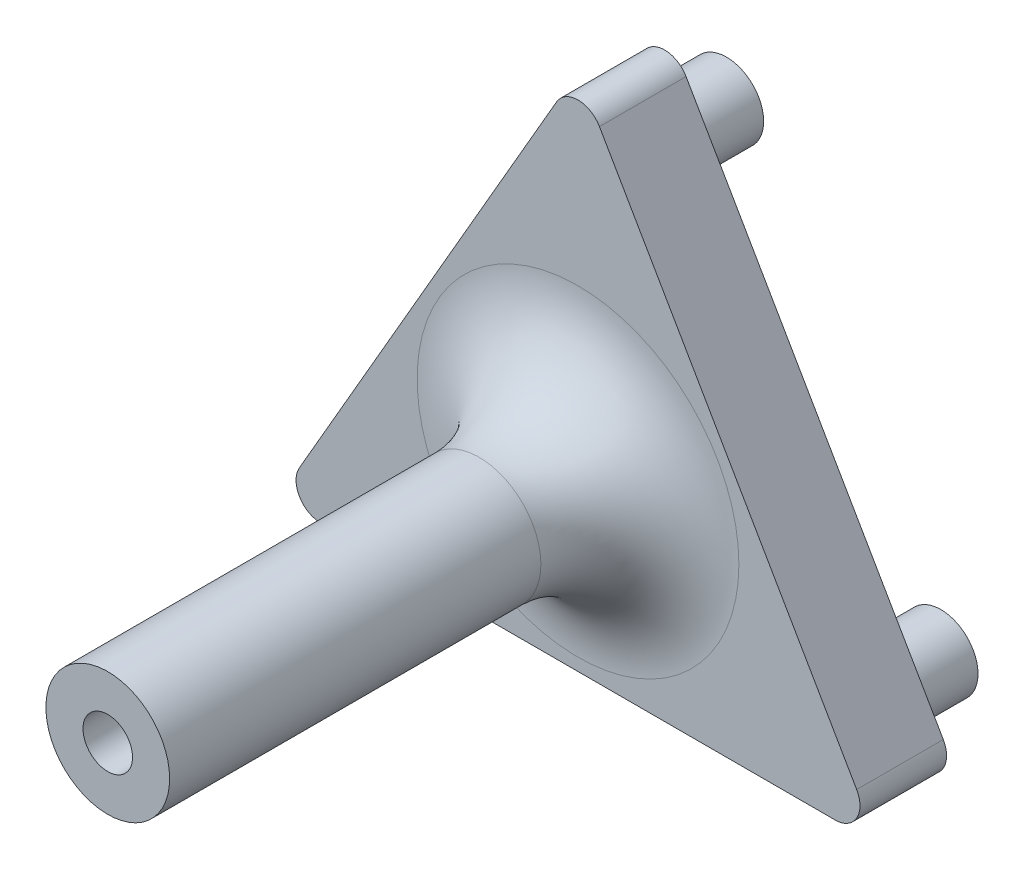
SolidWorks part; units mm, degrees
ref_plane "正面" through (0, 0, 0) normal (0, 0, 1) x (1, 0, 0)
ref_plane "平面" through (0, 0, 0) normal (0, 1, 0) x (1, 0, 0)
ref_plane "右側面" through (0, 0, 0) normal (1, 0, 0) x (0, 0, -1)
sketch "ｽｹｯﾁ1" plane through (0, 0, 0) normal (0, 0, 1) x (1, 0, 0)
  circle A0 centre (0, 0) radius 1
  circle A1 centre (0, 0) radius 2.5
  dimension "D1" = 2
  dimension "D2" = 1.5
extrude "ﾎﾞｽ - 押し出し2" add sketch "ｽｹｯﾁ1" along normal blind 24
sketch "ｽｹｯﾁ2" plane through (0, 0, 0) normal (0, 1, 0) x (1, 0, 0)
  line L0 (0, 0) -> (0, -24) construction
  dimension "D1" = 24
sketch "ｽｹｯﾁ3" plane through (0, 0, 0) normal (0, 0, 1) x (1, 0, 0)
  circle A0 centre (0, 0) radius 10
  circle A1 centre (0, 10) radius 1.5
  circle A2 centre (8.6603, -5) radius 1.5
  circle A3 centre (-8.6603, -5) radius 1.5
  point P10 (0, 0)
  dimension "D1" = 20
  dimension "D2" = 3
  dimension "D3" = 3
extrude "ﾎﾞｽ - 押し出し3" add sketch "ｽｹｯﾁ3" along normal blind 2 and the other way blind 1 separate body contours A2 | A3 | A1
sketch "ｽｹｯﾁ4" plane through (0, 0, 0) normal (0, 0, -1) x (-1, 0, 0)
  circle A0 centre (0, 0) radius 2.23
extrude "ｶｯﾄ - 押し出し1" cut sketch "ｽｹｯﾁ4" against normal blind 2
sketch "ｽｹｯﾁ5" plane through (0, 0, 2) normal (0, 0, 1) x (1, 0, 0)
  line L1 (0, 14) -> (-12.1244, -7)
  line L2 (-12.1244, -7) -> (12.1244, -7)
  line L3 (12.1244, -7) -> (0, 14)
  circle A0 centre (0, 10) radius 1.5
  circle A1 centre (-8.6603, -5) radius 1.5
  circle A2 centre (8.6603, -5) radius 1.5
  circle A3 centre (0, 0) radius 11.5
  circle A4 centre (0, 0) radius 7 construction
extrude "ﾎﾞｽ - 押し出し6" add sketch "ｽｹｯﾁ5" along normal blind 3 and the other way blind 0.5 contours L1 L2 L3
sketch "ｽｹｯﾁ10" plane through (0, 0, 0) normal (0, 0, -1) x (-1, 0, 0)
  circle A0 centre (0, 0) radius 2.35
  circle A1 centre (0, 0) radius 2.23
extrude "ｶｯﾄ - 押し出し2" cut sketch "ｽｹｯﾁ10" against normal blind 1
sketch "ｽｹｯﾁ11" plane through (0, 0, 1.5) normal (0, 0, -1) x (-1, 0, 0)
  circle A0 centre (0, 0) radius 3.7
  dimension "D1" = 7.4
extrude "ｶｯﾄ - 押し出し3" cut sketch "ｽｹｯﾁ11" against normal blind 2
sketch "ｽｹｯﾁ12" plane through (0, 0, 5) normal (0, 0, 1) x (1, 0, 0)
  circle A0 centre (0, 0) radius 1
  dimension "D1" = 2
extrude "ｶｯﾄ - 押し出し4" cut sketch "ｽｹｯﾁ12" against normal through all
fillet "ﾌｨﾚｯﾄ5" radius 1 3 edges at (-12.1244, -7, 3.25) (0, 14, 3.25) (12.1244, -7, 3.25)
fillet "ﾌｨﾚｯﾄ6" radius 4 1 edges at (2.5, 0, 5)
sketch "ｽｹｯﾁ14" plane through (0, 0, 0) normal (0, 0, -1) x (-1, 0, 0)
  circle A0 centre (0, 0) radius 2.75
  circle A1 centre (0, 0) radius 2.23
extrude "ｶｯﾄ - 押し出し5" cut sketch "ｽｹｯﾁ14" against normal blind 2
